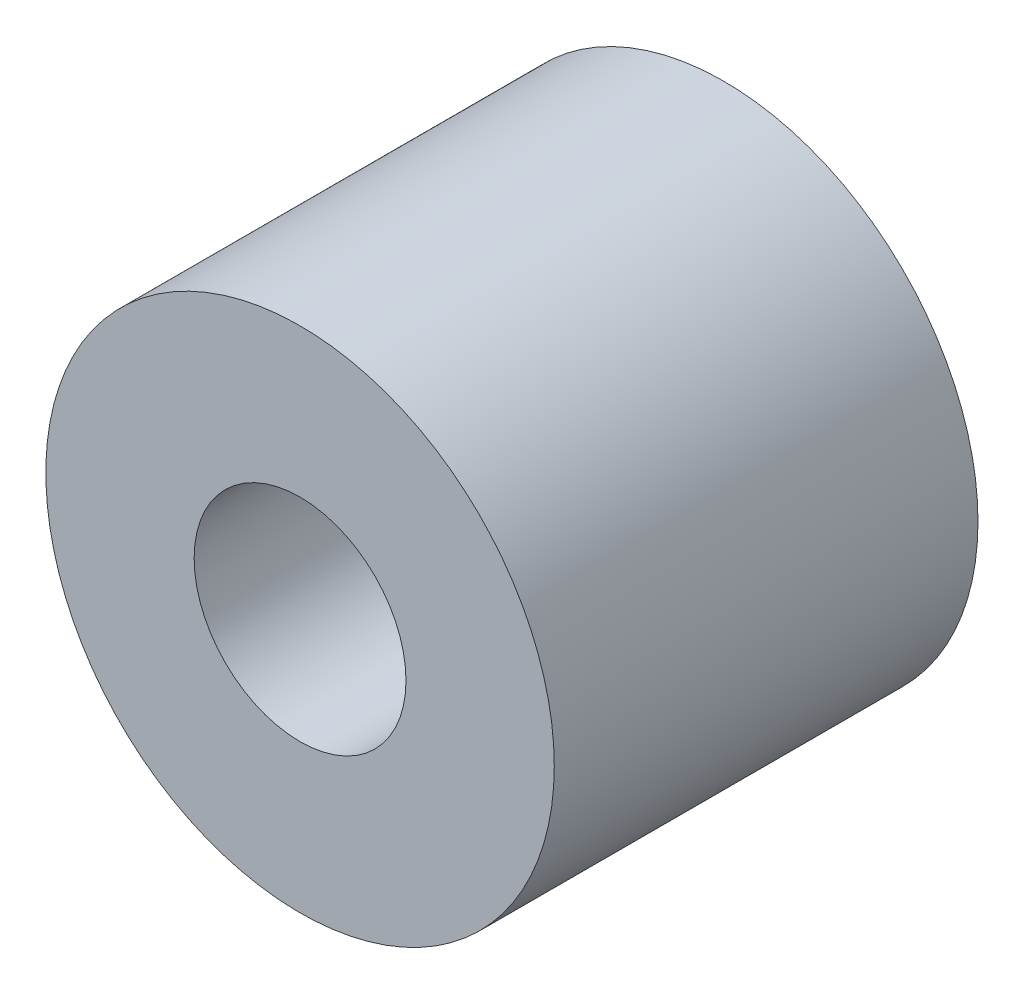
SolidWorks part; units mm, degrees
ref_plane "正面" through (0, 0, 0) normal (0, 0, 1) x (1, 0, 0)
ref_plane "平面" through (0, 0, 0) normal (0, 1, 0) x (1, 0, 0)
ref_plane "右側面" through (0, 0, 0) normal (1, 0, 0) x (0, 0, -1)
sketch "ｽｹｯﾁ1" plane through (0, 0, 0) normal (0, 0, 1) x (1, 0, 0)
  circle A0 centre (0, 0) radius 3
  circle A1 centre (0, 0) radius 1.25
  dimension "D1" = 2.5
  dimension "D2" = 6
extrude "ﾎﾞｽ - 押し出し1" add sketch "ｽｹｯﾁ1" along normal blind 5
